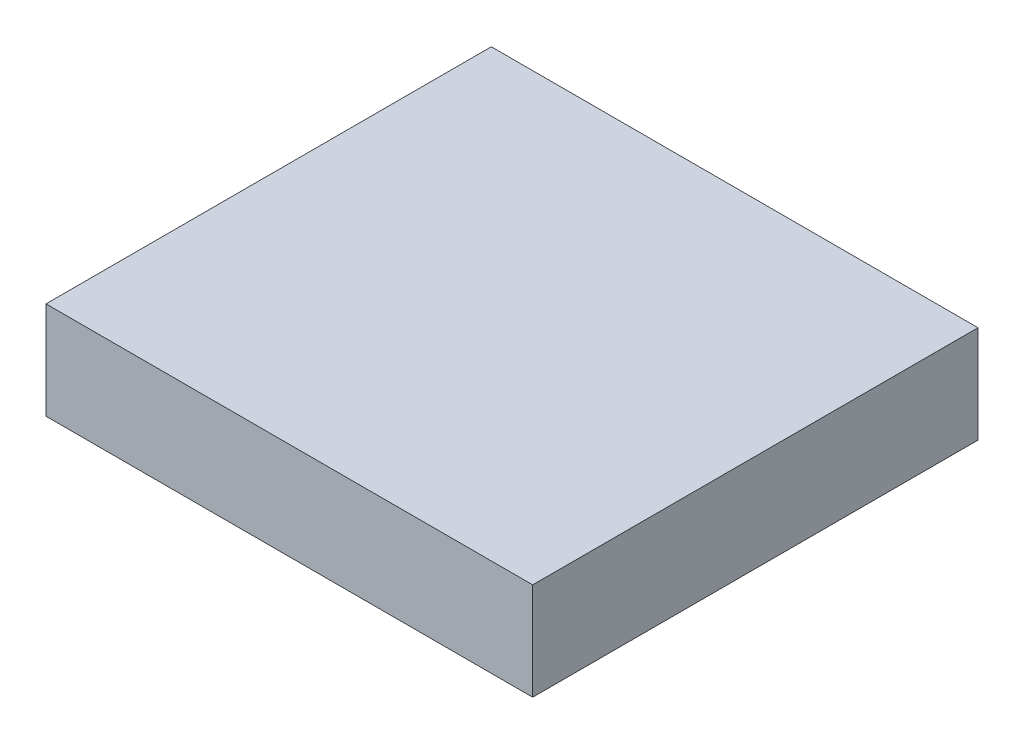
SolidWorks part; units mm, degrees
ref_plane "Front Plane" through (0, 0, 0) normal (0, 0, 1) x (1, 0, 0)
ref_plane "Top Plane" through (0, 0, 0) normal (0, 1, 0) x (1, 0, 0)
ref_plane "Right Plane" through (0, 0, 0) normal (1, 0, 0) x (0, 0, -1)
sketch "Sketch1" plane through (0, 0, 0) normal (0, 1, 0) x (1, 0, 0)
  line L1 (-10, -9.15) -> (10, -9.15)
  line L2 (-10, -9.15) -> (-10, 9.15)
  line L3 (-10, 9.15) -> (10, 9.15)
  line L4 (10, -9.15) -> (10, 9.15)
  line L5 (-10, -9.15) -> (10, 9.15) construction
  line L6 (-10, 9.15) -> (10, -9.15) construction
  point P0 (0, 0)
  dimension "D1" = 18.3
  dimension "D2" = 20
extrude "Boss-Extrude1" add sketch "Sketch1" along normal blind 4
